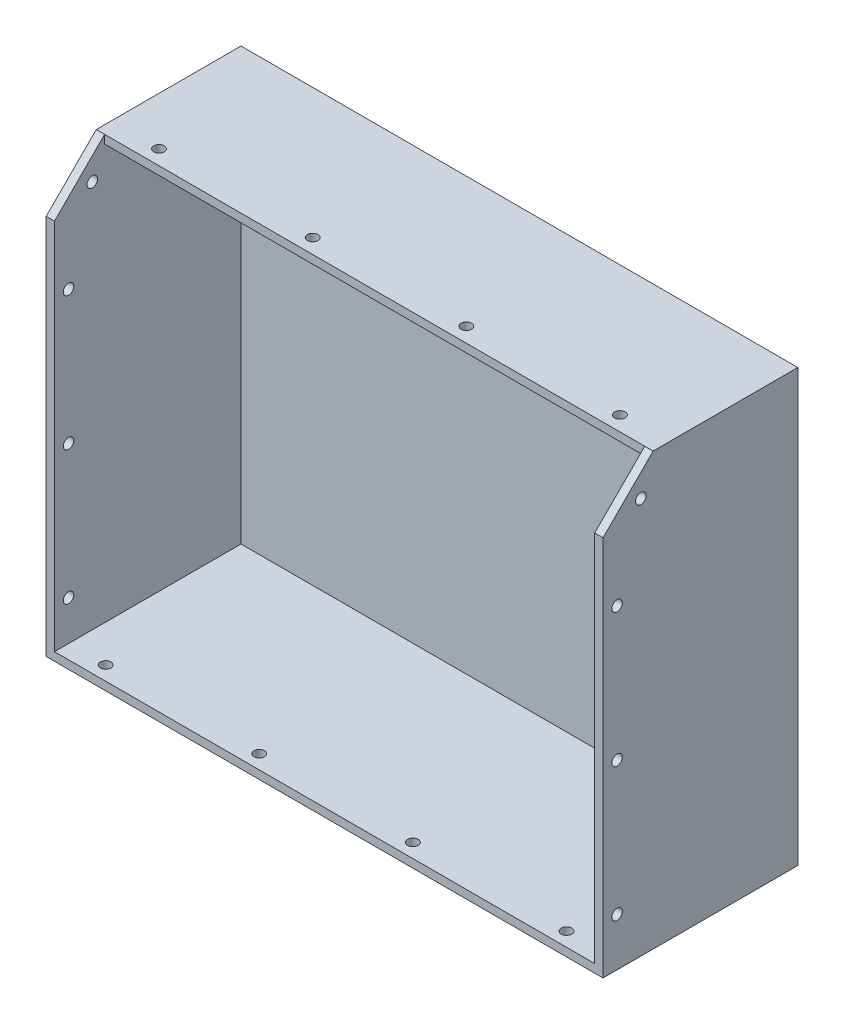
SolidWorks part; units mm, degrees
material "Custom Plastic"
ref_plane "X-Y Datum" through (0, 0, 0) normal (0, 0, 1) x (1, 0, 0)
ref_plane "X-Z Datum" through (0, 0, 0) normal (0, 1, 0) x (1, 0, 0)
ref_plane "Y-Z Datum" through (0, 0, 0) normal (1, 0, 0) x (0, 0, -1)
sketch "Sketch2" plane through (0, 0, 0) normal (0, 0, 1) x (1, 0, 0)
  line L1 (-105.8757, -82) -> (105.8757, -82)
  line L2 (-105.8757, -82) -> (-105.8757, 82)
  line L3 (-105.8757, 82) -> (105.8757, 82)
  line L4 (105.8757, -82) -> (105.8757, 82)
  line L5 (-105.8757, -82) -> (105.8757, 82) construction
  line L6 (-105.8757, 82) -> (105.8757, -82) construction
  point P0 (0, 0)
extrude "Boss-Extrude1" add sketch "Sketch2" along normal blind 74.0833
sketch "Sketch9" plane through (0, 0, 74.0833) normal (0, 0, 1) x (1, 0, 0)
  line L0 (-105.8757, -47.7482) -> (-102.7007, -47.7482)
  line L1 (-105.8757, 82) -> (-105.8757, -82) construction
  line L2 (-61.2665, -82) -> (-61.2665, -78.825)
  line L3 (-105.8757, -82) -> (105.8757, -82) construction
  line L4 (105.8757, -21.963) -> (102.7007, -21.963)
  line L5 (105.8757, -82) -> (105.8757, 82) construction
  line L6 (-87.7618, 82) -> (-87.7618, 78.825)
  line L7 (105.8757, 82) -> (-105.8757, 82) construction
  line L8 (-102.7007, 62.95) -> (-102.7007, 78.825)
  line L9 (-102.7007, -82) -> (-102.7007, 62.95)
  line L10 (-61.2665, -78.825) -> (-102.7007, -78.825)
  line L11 (-61.2665, -78.825) -> (102.7007, -78.825)
  line L12 (102.7007, -78.825) -> (102.7007, 82)
  line L13 (-102.7007, 78.825) -> (102.7007, 78.825)
extrude "Cut-Extrude7" cut sketch "Sketch9" against normal blind 70.9083
sketch "Sketch11" plane through (-105.8757, 0, 0) normal (-1, 0, 0) x (0, 0, 1)
  line L0 (74.0833, 62.95) -> (55.0333, 62.95)
  line L1 (74.0833, 82) -> (74.0833, -82) construction
  line L2 (55.0333, 62.95) -> (55.0333, 82)
  line L3 (74.0833, 82) -> (0, 82) construction
  line L4 (55.0333, 82) -> (74.0833, 62.95)
  line L5 (55.0333, 82) -> (74.0833, 82)
  line L6 (74.0833, 82) -> (74.0833, 62.95)
  line L7 (55.0333, 79.6238) -> (58.2083, 79.6238)
  line L8 (58.2083, 78.825) -> (58.2083, 82)
  line M5 (74.0833, -82) -> (74.0833, 82)
  line M6 (74.0833, 82) -> (0, 82)
extrude "Cut-Extrude9" cut sketch "Sketch11" against normal up to next contours L8 L4 M5 M6
sketch "Sketch13" plane through (-105.8757, 0, 0) normal (-1, 0, 0) x (0, 0, 1)
  line L0 (58.2083, 78.825) -> (55.0333, 82)
  line L1 (58.2083, 82) -> (0, 82) construction
  line L2 (55.0333, 82) -> (58.2083, 82)
  line L3 (58.2083, 82) -> (58.2083, 78.825)
extrude "Cut-Extrude10" cut sketch "Sketch13" against normal blind 3.175
sketch "Sketch14" plane through (0, 0, 58.2083) normal (0, 0, 1) x (1, 0, 0)
  line L1 (-102.7007, 82) -> (102.7007, 82)
  line L2 (-102.7007, 82) -> (-102.7007, 78.825)
  line L3 (-102.7007, 78.825) -> (102.7007, 78.825)
  line L4 (102.7007, 82) -> (102.7007, 78.825)
extrude "Cut-Extrude11" cut sketch "Sketch14" against normal blind 3.175
sketch "Sketch15" plane through (105.8757, 0, 0) normal (1, 0, 0) x (0, 0, -1)
  line L0 (-58.2083, 78.825) -> (-55.0333, 82)
  line L1 (-55.0333, 82) -> (-58.2083, 82)
  line L2 (-58.2083, 82) -> (-58.2083, 79.2157)
  line L3 (-58.2083, 82) -> (-58.2083, 78.825) construction
extrude "Cut-Extrude12" cut sketch "Sketch15" against normal blind 3.175 and the other way through all
sketch "Sketch16" plane through (-105.8757, 0, 0) normal (-1, 0, 0) x (0, 0, 1)
  line L0 (68.7493, -68.9821) -> (74.0833, -68.9821)
  line L2 (74.0833, 62.95) -> (74.0833, -82) construction
  line L3 (68.7493, -82) -> (68.7493, -63.712)
  line L4 (74.0833, -82) -> (0, -82) construction
  circle A0 centre (68.7493, -63.712) radius 2
  dimension "D1" = 5.334
  dimension "D2" = 18.288
extrude "Cut-Extrude13" cut sketch "Sketch16" against normal through all
pattern_linear "LPattern1" count 3 spacing 50.8 along (0, 1, 0) of "Cut-Extrude13"
sketch "Sketch18" plane through (0, -82, 0) normal (0, -1, 0) x (1, 0, 0)
  line L0 (-88.6037, 74.0833) -> (-88.6037, 68.7493)
  line L1 (-105.8757, 74.0833) -> (105.8757, 74.0833) construction
  line L2 (-88.6037, 68.7493) -> (-105.8757, 68.7493)
  line L3 (-105.8757, 74.0833) -> (-105.8757, 0) construction
  circle A0 centre (-88.6037, 68.7493) radius 2
  dimension "D1" = 5.334
  dimension "D2" = 17.272
extrude "Cut-Extrude14" cut sketch "Sketch18" against normal up to next contours A0
pattern_linear "LPattern2" count 4 spacing 58.42 along (1, 0, 0) of "Cut-Extrude14"
sketch "Sketch19" plane through (0, 82, 0) normal (0, 1, 0) x (1, 0, 0)
  line L0 (-105.8757, -49.4453) -> (-87.5877, -49.4453)
  line L1 (-105.8757, -55.0333) -> (-105.8757, 0) construction
  line L2 (-96.7317, -49.4453) -> (-96.7317, -55.0333)
  line L3 (102.7007, -55.0333) -> (-102.7007, -55.0333) construction
  circle A0 centre (-87.5877, -49.4453) radius 2
  dimension "D1" = 18.288
  dimension "D2" = 5.588
extrude "Cut-Extrude15" cut sketch "Sketch19" against normal up to next
pattern_linear "LPattern3" count 4 spacing 58.42 along (1, 0, 0) of "Cut-Extrude15"
sketch "Sketch20" plane through (-105.8757, 0, 0) normal (-1, 0, 0) x (0, 0, 1)
  line L2 (64.0136, 73.0197) -> (59.7031, 68.7092)
  line L3 (55.0333, 82) -> (74.0833, 62.95) construction
  line L4 (64.0136, 73.0197) -> (55.0333, 82)
  circle A0 centre (59.7031, 68.7092) radius 2
  dimension "D1" = 6.096
  dimension "D2" = 12.7
extrude "Cut-Extrude16" cut sketch "Sketch20" against normal through all
